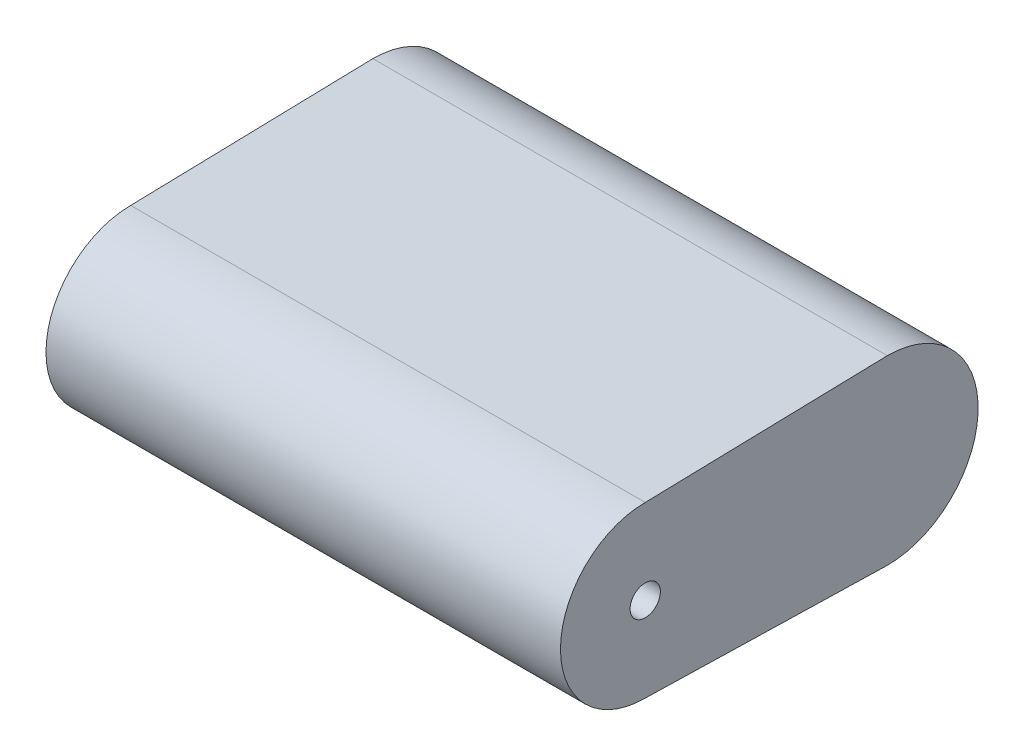
SolidWorks part; units mm, degrees
ref_plane "Alzado" through (0, 0, 0) normal (0, 0, 1) x (1, 0, 0)
ref_plane "Planta" through (0, 0, 0) normal (0, 1, 0) x (1, 0, 0)
ref_plane "Vista lateral" through (0, 0, 0) normal (1, 0, 0) x (0, 0, -1)
sketch "Croquis1" plane through (0, 0, 0) normal (1, 0, 0) x (0, 0, -1)
  line L0 (0, 0) -> (40, 0) construction
  line L1 (0, 14) -> (40, 15)
  line L2 (0, -14) -> (40, -15)
  arc A0 (0, 14) -> (0, -14) centre (0, 0) ccw
  arc A1 (40, -15) -> (40, 15) centre (40, 0) ccw
  circle A2 centre (0, 0) radius 2.5
  dimension "D2" = 28
  dimension "D3" = 30
  dimension "D4" = 5
  dimension "D1" = 40
extrude "Saliente-Extruir1" add sketch "Croquis1" along normal mid plane 85
